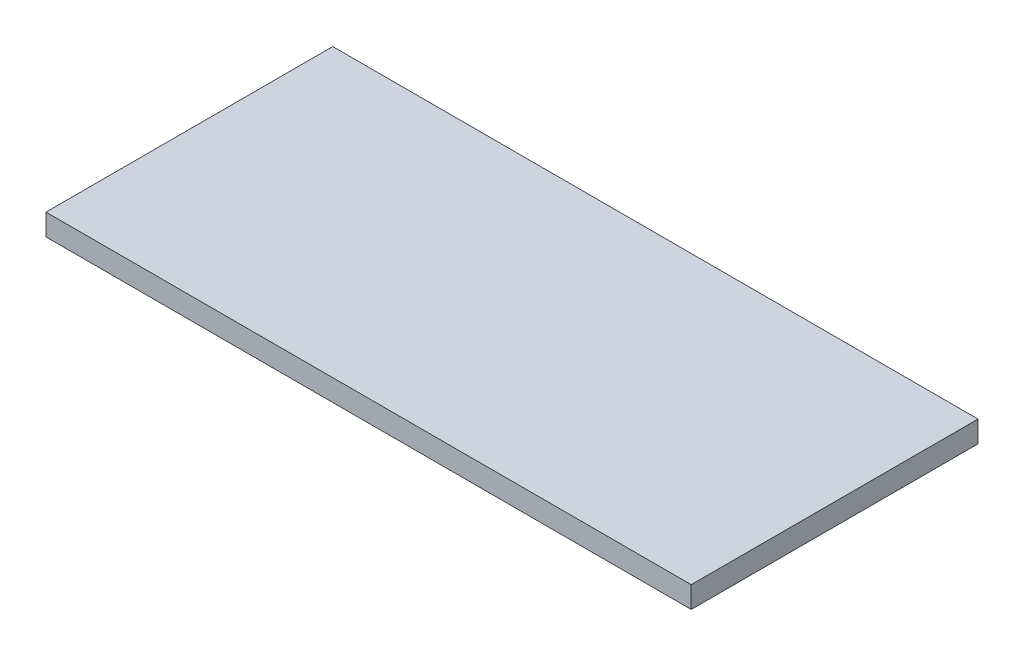
SolidWorks part; units mm, degrees
ref_plane "Front" through (0, 0, 0) normal (0, 0, 1) x (1, 0, 0)
ref_plane "Top" through (0, 0, 0) normal (0, 1, 0) x (1, 0, 0)
ref_plane "Right" through (0, 0, 0) normal (1, 0, 0) x (0, 0, -1)
sketch "Sketch1" plane through (0, 0, 0) normal (0, 1, 0) x (1, 0, 0)
  line L1 (-49.0909, 22.9855) -> (40.9091, 22.9855)
  line L2 (-49.0909, 22.9855) -> (-49.0909, -17.0145)
  line L3 (-49.0909, -17.0145) -> (40.9091, -17.0145)
  line L4 (40.9091, 22.9855) -> (40.9091, -17.0145)
  dimension "D1" = 90
  dimension "D2" = 40
extrude "Boss-Extrude1" add sketch "Sketch1" along normal blind 3
